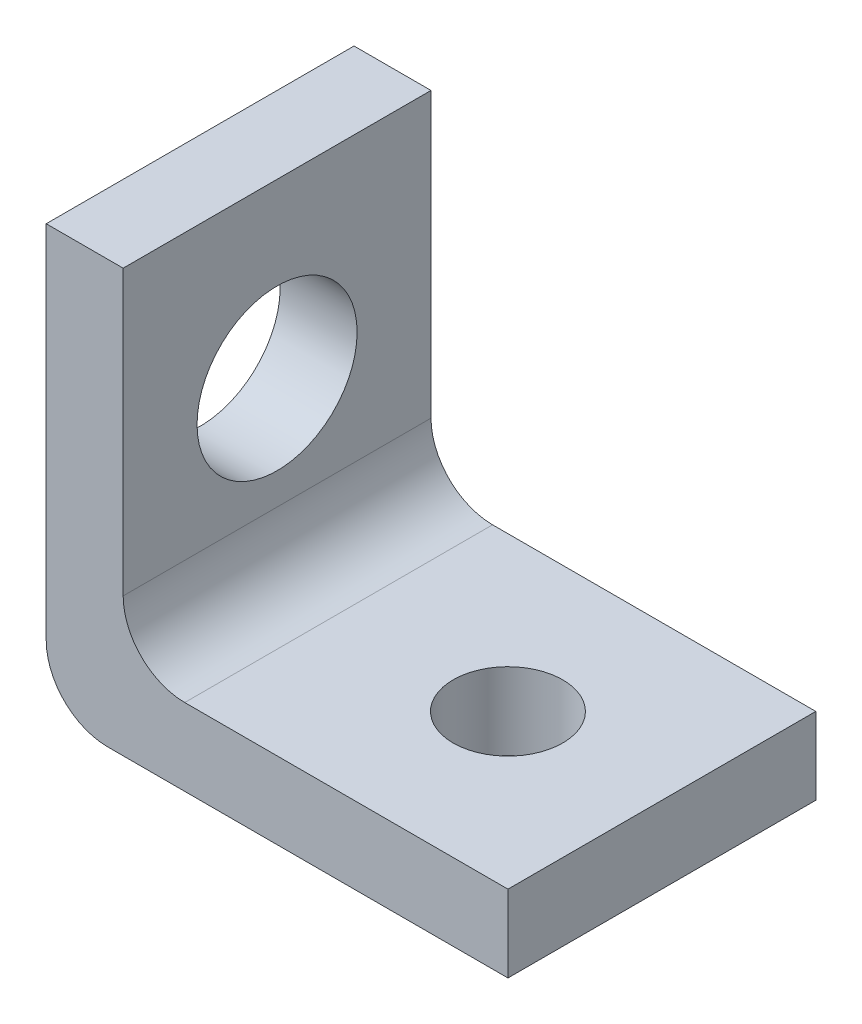
SolidWorks part; units mm, degrees
ref_plane "Front Plane" through (0, 0, 0) normal (0, 0, 1) x (1, 0, 0)
ref_plane "Top Plane" through (0, 0, 0) normal (0, 1, 0) x (1, 0, 0)
ref_plane "Right Plane" through (0, 0, 0) normal (1, 0, 0) x (0, 0, -1)
sketch "Sketch1" plane through (0, 0, 0) normal (0, 0, 1) x (1, 0, 0)
  line L0 (0, 1.27) -> (0, 7.1247)
  line L1 (0, 7.1247) -> (-1.5875, 7.1247)
  line L2 (-1.5875, 7.1247) -> (-1.5875, -0.3175)
  line L3 (-0.3175, -1.5875) -> (7.9375, -1.5875)
  line L4 (7.9375, -1.5875) -> (7.9375, 0)
  line L5 (7.9375, 0) -> (1.27, 0)
  arc A0 (0, 1.27) -> (1.27, 0) centre (1.27, 1.27) ccw
  arc A1 (-1.5875, -0.3175) -> (-0.3175, -1.5875) centre (-0.3175, -0.3175) ccw
  point P9 (0, 0)
  point P12 (-1.5875, -1.5875)
  dimension "D5" = 1.27
  dimension "D1" = 9.525
  dimension "D2" = 8.7122
  dimension "D3" = 1.5875
  dimension "D4" = 1.5875
extrude "Boss-Extrude1" add sketch "Sketch1" along normal blind 6.35
hole_wizard "#4 Clearance Hole1" positions "Sketch4" profile "Sketch2" hole size "#4" standard "Progressive"
sketch "Sketch4" plane through (0, 0, 0) normal (1, 0, 0) x (0, 0, -1)
  line L0 (-6.35, -1.5875) -> (0, -1.5875) construction
  line L1 (0, 1.27) -> (0, 7.1247) construction
  point P0 (-3.175, 3.5687)
  dimension "D1" = 5.1562
  dimension "D2" = 3.175
sketch "Sketch2" plane through (0, 3.5687, 3.175) normal (0, 1, 0) x (0, 0, -1)
  line L0 (0, 0) -> (0, 58.142)
  line L1 (0, 58.142) -> (1.651, 57.15)
  line L2 (1.651, 57.15) -> (1.651, 0)
  line L5 (1.651, 0) -> (0, 0)
  line L10 (0, 58.142) -> (-1.651, 57.15) construction
  line L11 (0, -6.35) -> (0, 107.95) construction
  dimension "Hole Dia." = 3.302
  dimension "Hole Depth" = 57.15
  dimension "Drill Angle" = 118
hole_wizard "#4-40 Tapped Hole1" positions "Sketch6" profile "Sketch5" tap size "#4-40" standard "Superior" end condition through all
sketch "Sketch6" plane through (0, 0, 0) normal (0, 1, 0) x (1, 0, 0)
  line L0 (-1.5875, -6.35) -> (-1.5875, 0) construction
  line L1 (7.9375, -6.35) -> (1.27, -6.35) construction
  point P0 (4.7625, -3.175)
  dimension "D1" = 6.35
  dimension "D2" = 3.175
sketch "Sketch5" plane through (4.7625, 0, 3.175) normal (1, 0, 0) x (0, 0, 1)
  line L0 (0, 0) -> (0, 1.5875)
  line L1 (0, 1.5875) -> (1.1303, 1.5875)
  line L2 (1.1303, 1.5875) -> (1.1303, 0)
  line L5 (1.1303, 0) -> (0, 0)
  line L11 (0, -6.35) -> (0, 107.95) construction
  dimension "Thread Major Dia." = 2.2606
  dimension "Thru Tap Drill Depth" = 1.5875
